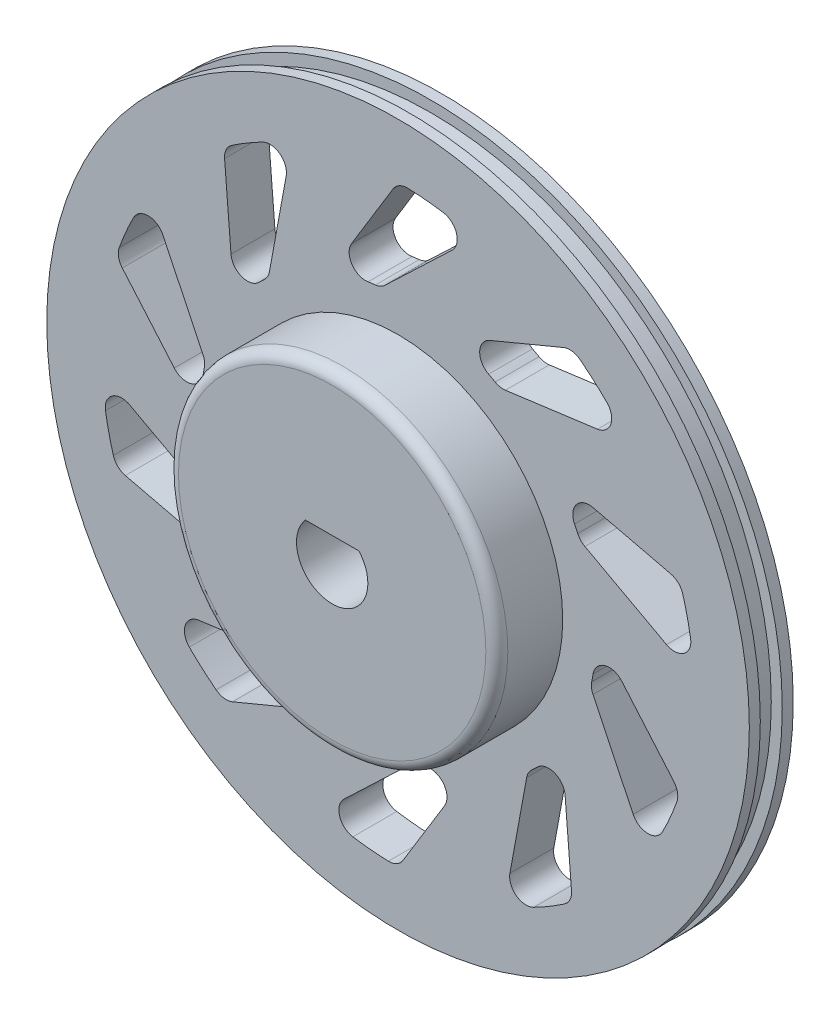
SolidWorks part; units mm, degrees
material "ABS"
ref_plane "Спереди" through (0, 0, 0) normal (0, 0, 1) x (1, 0, 0)
ref_plane "Сверху" through (0, 0, 0) normal (0, 1, 0) x (1, 0, 0)
ref_plane "Справа" through (0, 0, 0) normal (1, 0, 0) x (0, 0, -1)
sketch "Эскиз1" plane through (0, 0, 0) normal (0, 0, 1) x (1, 0, 0)
  circle A0 centre (0, 0) radius 31
  dimension "D1" = 62
extrude "Бобышка-Вытянуть2" add sketch "Эскиз1" along normal blind 2
sketch "Эскиз2" plane through (0, 0, 2) normal (0, 0, 1) x (1, 0, 0)
  circle A0 centre (0, 0) radius 32
  circle A1 centre (0, 0) radius 31 construction
  dimension "D1" = 1
extrude "Бобышка-Вытянуть3" add sketch "Эскиз2" along normal blind 1
sketch "Эскиз3" plane through (0, 0, 0) normal (0, 0, -1) x (-1, 0, 0)
  circle A0 centre (0, 0) radius 32
  circle A1 centre (0, 0) radius 32 construction
extrude "Бобышка-Вытянуть4" add sketch "Эскиз3" along normal blind 1
sketch "Эскиз4" plane through (0, 0, -1) normal (0, 0, -1) x (-1, 0, 0)
  line L0 (2.4372, 2.15) -> (-2.4372, 2.15)
  line L1 (0, -3.25) -> (-5.9785, -3.25) construction
  arc A0 (-2.4372, 2.15) -> (2.4372, 2.15) centre (0, 0) ccw
  dimension "D1" = 6.5
  dimension "D2" = 5.4
sketch "Эскиз6" plane through (0, 0, 3) normal (0, 0, 1) x (1, 0, 0)
  circle A0 centre (0, 0) radius 15
  dimension "D1" = 30
extrude "Бобышка-Вытянуть6" add sketch "Эскиз6" along normal blind 6
extrude "Вырез-Вытянуть4" cut sketch "Эскиз4" against normal through all
sketch "Эскиз7" plane through (0, 0, 3) normal (0, 0, 1) x (1, 0, 0)
  line L0 (0, 0) -> (0, 27) construction
  line L1 (0, 0) -> (-9.2345, 25.3717) construction
  line L2 (-1.1969, 18.2857) -> (4.9248, 24.1152)
  line L3 (4.9248, 24.1152) -> (6.9881, 26.08) construction
  line L4 (-4.2389, 20.0558) -> (-0.4469, 26.2679)
  line L5 (-0.4469, 26.2679) -> (0, 27) construction
  line L6 (8.3592, 18.717) -> (15.0783, 21.5139)
  line L7 (9.7797, 15.4969) -> (18.1589, 16.6149)
  line L8 (17.7643, 10.229) -> (24.8442, 8.5422)
  line L9 (17.0208, 6.7889) -> (24.4568, 2.7682)
  line L10 (20.3841, -2.1662) -> (25.1204, -7.6922)
  line L11 (17.7606, -4.5123) -> (21.4131, -12.1358)
  line L12 (15.2178, -13.7339) -> (15.8014, -20.9885)
  line L13 (11.7164, -14.0899) -> (10.1903, -22.4044)
  line L14 (4.2389, -20.0558) -> (0.4469, -26.2679)
  line L15 (1.1969, -18.2857) -> (-4.9248, -24.1152)
  line L16 (-8.3592, -18.717) -> (-15.0783, -21.5139)
  line L17 (-9.7797, -15.4969) -> (-18.1589, -16.6149)
  line L18 (-17.7643, -10.229) -> (-24.8442, -8.5422)
  line L19 (-17.0208, -6.7889) -> (-24.4568, -2.7682)
  line L20 (-20.3841, 2.1662) -> (-25.1204, 7.6922)
  line L21 (-17.7606, 4.5123) -> (-21.4131, 12.1358)
  line L22 (-15.2178, 13.7339) -> (-15.8014, 20.9885)
  line L23 (-11.7164, 14.0899) -> (-10.1903, 22.4044)
  circle A0 centre (0, 0) radius 18 construction
  circle A1 centre (0, 0) radius 27 construction
  circle A2 centre (0, 0) radius 32 construction
  circle A3 centre (0, 0) radius 15 construction
  arc A4 (0.8825, 26.9856) -> (4.1193, 26.6839) centre (0, 0) cw
  arc A5 (-2.731, 17.7916) -> (-2.0597, 17.8818) centre (0, 0) cw
  arc A6 (-2.731, 17.7916) -> (-4.2389, 20.0558) centre (-2.9585, 19.2743) cw
  arc A7 (4.1193, 26.6839) -> (4.9248, 24.1152) centre (3.8904, 25.2015) cw
  arc A8 (-2.0597, 17.8818) -> (-1.1969, 18.2857) centre (-2.2313, 19.3719) ccw
  arc A9 (0.8825, 26.9856) -> (-0.4469, 26.2679) centre (0.8334, 25.4864) ccw
  arc A10 (16.5756, 21.3131) -> (15.0783, 21.5139) centre (15.6548, 20.129) ccw
  arc A11 (16.5756, 21.3131) -> (19.017, 19.1665) centre (0, 0) cw
  arc A12 (19.017, 19.1665) -> (18.1589, 16.6149) centre (17.9605, 18.1017) cw
  arc A13 (8.2483, 15.9989) -> (8.8443, 15.6773) centre (0, 0) cw
  arc A14 (8.8443, 15.6773) -> (9.7797, 15.4969) centre (9.5813, 16.9838) ccw
  arc A15 (8.2483, 15.9989) -> (8.3592, 18.717) centre (8.9356, 17.3322) cw
  arc A16 (25.9375, 7.4997) -> (24.8442, 8.5422) centre (24.4965, 7.0831) ccw
  arc A17 (25.9375, 7.4997) -> (26.6508, 4.3281) centre (0, 0) cw
  arc A18 (26.6508, 4.3281) -> (24.4568, 2.7682) centre (25.1702, 4.0877) cw
  arc A19 (16.0769, 8.0952) -> (16.3701, 7.4846) centre (0, 0) cw
  arc A20 (16.3701, 7.4846) -> (17.0208, 6.7889) centre (17.7343, 8.1084) ccw
  arc A21 (16.0769, 8.0952) -> (17.7643, 10.229) centre (17.4167, 8.7698) cw
  arc A22 (25.3921, -9.1783) -> (25.1204, -7.6922) centre (23.9814, -8.6684) ccw
  arc A23 (25.3921, -9.1783) -> (24.105, -12.1635) centre (0, 0) cw
  arc A24 (24.105, -12.1635) -> (21.4131, -12.1358) centre (22.7658, -11.4877) cw
  arc A25 (17.7648, -2.9006) -> (17.6431, -3.5669) centre (0, 0) cw
  arc A26 (17.6431, -3.5669) -> (17.7606, -4.5123) centre (19.1133, -3.8641) ccw
  arc A27 (17.7648, -2.9006) -> (20.3841, -2.1662) centre (19.2451, -3.1423) cw
  arc A28 (15.1478, -22.3505) -> (15.8014, -20.9885) centre (14.3063, -21.1088) ccw
  arc A29 (15.1478, -22.3505) -> (12.3518, -24.009) centre (0, 0) cw
  arc A30 (12.3518, -24.009) -> (10.1903, -22.4044) centre (11.6656, -22.6752) cw
  arc A31 (12.667, -12.7885) -> (12.177, -13.256) centre (0, 0) cw
  arc A32 (12.177, -13.256) -> (11.7164, -14.0899) centre (13.1917, -14.3607) ccw
  arc A33 (12.667, -12.7885) -> (15.2178, -13.7339) centre (13.7226, -13.8542) cw
  arc A34 (-0.8825, -26.9856) -> (0.4469, -26.2679) centre (-0.8334, -25.4864) ccw
  arc A35 (-0.8825, -26.9856) -> (-4.1193, -26.6839) centre (0, 0) cw
  arc A36 (-4.1193, -26.6839) -> (-4.9248, -24.1152) centre (-3.8904, -25.2015) cw
  arc A37 (2.731, -17.7916) -> (2.0597, -17.8818) centre (0, 0) cw
  arc A38 (2.0597, -17.8818) -> (1.1969, -18.2857) centre (2.2313, -19.3719) ccw
  arc A39 (2.731, -17.7916) -> (4.2389, -20.0558) centre (2.9585, -19.2743) cw
  arc A40 (-16.5756, -21.3131) -> (-15.0783, -21.5139) centre (-15.6548, -20.129) ccw
  arc A41 (-16.5756, -21.3131) -> (-19.017, -19.1665) centre (0, 0) cw
  arc A42 (-19.017, -19.1665) -> (-18.1589, -16.6149) centre (-17.9605, -18.1017) cw
  arc A43 (-8.2483, -15.9989) -> (-8.8443, -15.6773) centre (0, 0) cw
  arc A44 (-8.8443, -15.6773) -> (-9.7797, -15.4969) centre (-9.5813, -16.9838) ccw
  arc A45 (-8.2483, -15.9989) -> (-8.3592, -18.717) centre (-8.9356, -17.3322) cw
  arc A46 (-25.9375, -7.4997) -> (-24.8442, -8.5422) centre (-24.4965, -7.0831) ccw
  arc A47 (-25.9375, -7.4997) -> (-26.6508, -4.3281) centre (0, 0) cw
  arc A48 (-26.6508, -4.3281) -> (-24.4568, -2.7682) centre (-25.1702, -4.0877) cw
  arc A49 (-16.0769, -8.0952) -> (-16.3701, -7.4846) centre (0, 0) cw
  arc A50 (-16.3701, -7.4846) -> (-17.0208, -6.7889) centre (-17.7343, -8.1084) ccw
  arc A51 (-16.0769, -8.0952) -> (-17.7643, -10.229) centre (-17.4167, -8.7698) cw
  arc A52 (-25.3921, 9.1783) -> (-25.1204, 7.6922) centre (-23.9814, 8.6684) ccw
  arc A53 (-25.3921, 9.1783) -> (-24.105, 12.1635) centre (0, 0) cw
  arc A54 (-24.105, 12.1635) -> (-21.4131, 12.1358) centre (-22.7658, 11.4877) cw
  arc A55 (-17.7648, 2.9006) -> (-17.6431, 3.5669) centre (0, 0) cw
  arc A56 (-17.6431, 3.5669) -> (-17.7606, 4.5123) centre (-19.1133, 3.8641) ccw
  arc A57 (-17.7648, 2.9006) -> (-20.3841, 2.1662) centre (-19.2451, 3.1423) cw
  arc A58 (-15.1478, 22.3505) -> (-15.8014, 20.9885) centre (-14.3063, 21.1088) ccw
  arc A59 (-15.1478, 22.3505) -> (-12.3518, 24.009) centre (0, 0) cw
  arc A60 (-12.3518, 24.009) -> (-10.1903, 22.4044) centre (-11.6656, 22.6752) cw
  arc A61 (-12.667, 12.7885) -> (-12.177, 13.256) centre (0, 0) cw
  arc A62 (-12.177, 13.256) -> (-11.7164, 14.0899) centre (-13.1917, 14.3607) ccw
  arc A63 (-12.667, 12.7885) -> (-15.2178, 13.7339) centre (-13.7226, 13.8542) cw
  point P16 (-6.1564, 16.9145)
  point P22 (-1.5688, 17.9315)
  point P136 (0, 0)
  dimension "D1" = 5
  dimension "D2" = 3
  dimension "D5" = 1.5
  dimension "D3" = 15
  dimension "D4" = 15
  dimension "D6" = 20
  dimension "D7" = 10
extrude "Вырез-Вытянуть5" cut sketch "Эскиз7" against normal through all
fillet "Скругление1" radius 1 1 edges at (15, 0, 9)
